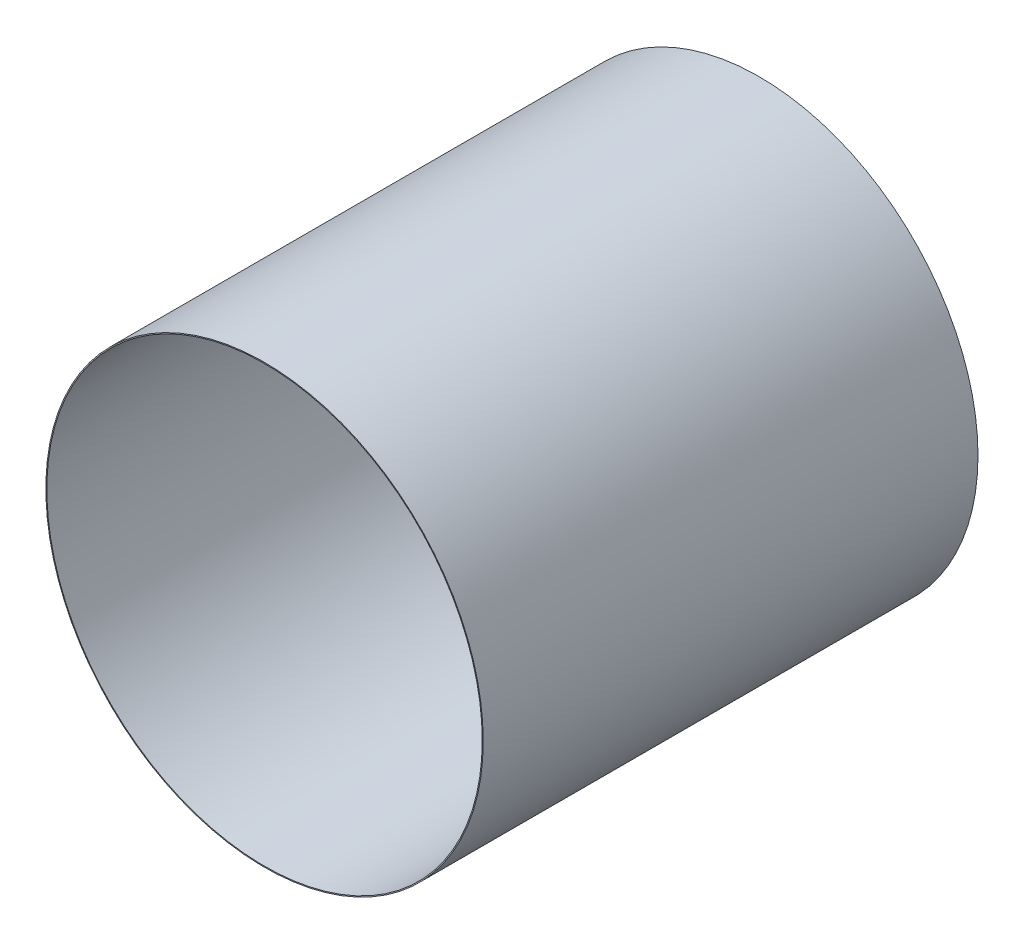
SolidWorks part; units mm, degrees
ref_plane "Front Plane" through (0, 0, 0) normal (0, 0, 1) x (1, 0, 0)
ref_plane "Top Plane" through (0, 0, 0) normal (0, 1, 0) x (1, 0, 0)
ref_plane "Right Plane" through (0, 0, 0) normal (1, 0, 0) x (0, 0, -1)
sketch "Sketch1" plane through (0, 0, 0) normal (0, 0, 1) x (1, 0, 0)
  circle A0 centre (0, 0) radius 11.05
  circle A1 centre (0, 0) radius 11
  dimension "D1" = 22
  dimension "D2" = 22.1
extrude "Boss-Extrude1" add sketch "Sketch1" along normal blind 25
